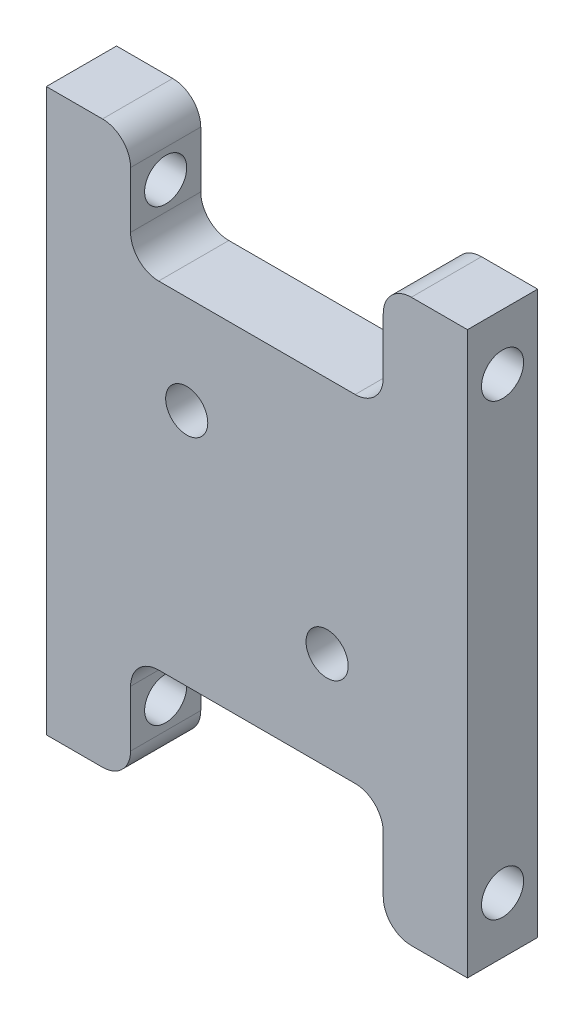
SolidWorks part; units mm, degrees
ref_plane "前视基准面" through (0, 0, 0) normal (0, 0, 1) x (1, 0, 0)
ref_plane "上视基准面" through (0, 0, 0) normal (0, 1, 0) x (1, 0, 0)
ref_plane "右视基准面" through (0, 0, 0) normal (1, 0, 0) x (0, 0, -1)
sketch "草图1" plane through (0, 0, 0) normal (0, 0, 1) x (1, 0, 0)
  line L0 (9, 20) -> (9, 12)
  line L1 (-15, 20) -> (-9, 20)
  line L2 (-15, 20) -> (-15, -20)
  line L3 (-15, -20) -> (-9, -20)
  line L4 (15, 20) -> (15, -20)
  line L5 (-15, 20) -> (15, -20) construction
  line L6 (-15, -20) -> (15, 20) construction
  line L7 (9, 12) -> (-9, 12)
  line L8 (-9, 12) -> (-9, 20)
  line L9 (9, -20) -> (9, -12)
  line L10 (9, -12) -> (-9, -12)
  line L11 (-9, -12) -> (-9, -20)
  line L12 (9, 20) -> (15, 20)
  line L13 (9, -20) -> (15, -20)
  point P0 (0, 0)
  dimension "D1" = 6
  dimension "D2" = 30
  dimension "D3" = 6
  dimension "D4" = 6
  dimension "D5" = 40
  dimension "D6" = 8
extrude "凸台-拉伸1" add sketch "草图1" along normal blind 5
fillet "圆角1" radius 2 8 edges at (-9, -20, 2.5) (9, -20, 2.5) (9, -12, 2.5) (-9, -12, 2.5) (9, 20, 2.5) (9, 12, 2.5) (-9, 12, 2.5) (-9, 20, 2.5)
sketch "草图2" plane through (0, 0, 5) normal (0, 0, 1) x (1, 0, 0)
  circle A0 centre (-5, 5) radius 1.5
  circle A1 centre (5, -5) radius 1.5
  dimension "D1" = 3
  dimension "D2" = 3
  dimension "D3" = 5
  dimension "D4" = 5
  dimension "D5" = 5
  dimension "D6" = 5
extrude "切除-拉伸1" cut sketch "草图2" against normal through all
sketch "草图6" plane through (15, 0, 0) normal (1, 0, 0) x (0, 0, -1)
  line L0 (-5, 20) -> (0, 20) construction
  line L1 (0, -20) -> (0, 20) construction
  circle A0 centre (-2.5, 16) radius 1.5
  circle A1 centre (-2.5, -16) radius 1.5
  dimension "D1" = 3
  dimension "D3" = 2.5
  dimension "D2" = 4
extrude "切除-拉伸2" cut sketch "草图6" against normal through all
